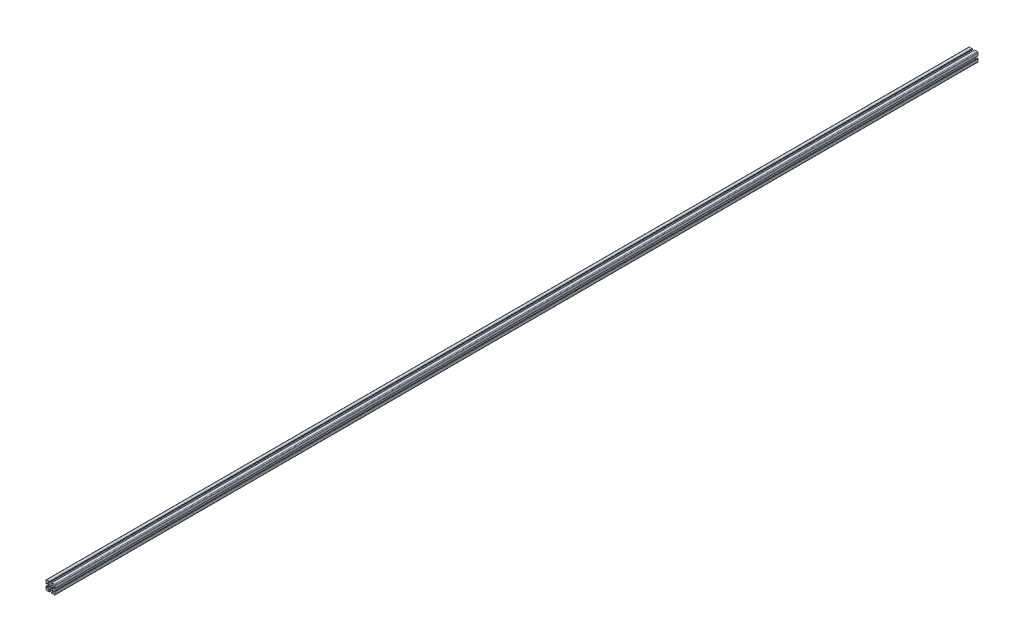
SolidWorks part; units mm, degrees
material "6061 Alloy"
ref_plane "Front Plane" through (0, 0, 0) normal (0, 0, 1) x (1, 0, 0)
ref_plane "Top Plane" through (0, 0, 0) normal (0, 1, 0) x (1, 0, 0)
ref_plane "Right Plane" through (0, 0, 0) normal (1, 0, 0) x (0, 0, -1)
sketch "Sketch1" plane through (0, 0, 0) normal (0, 0, 1) x (1, 0, 0)
  line L0 (0, 19.7407) -> (0, -19.7407) construction
  line L1 (19.0335, 0) -> (-20.7246, 0) construction
  line L2 (-8.715, -15.5246) -> (-5.63, -15.5246)
  line L3 (-10.285, -13.9546) -> (-10.285, -13.4925)
  line L4 (-6.2171, -9.1098) -> (-10.0624, -12.9551)
  line L5 (2.7773, -7.685) -> (-2.7773, -7.685)
  line L6 (10.0624, -12.9551) -> (6.2171, -9.1098)
  line L7 (10.285, -13.9546) -> (10.285, -13.4925)
  line L8 (5.63, -15.5246) -> (8.715, -15.5246)
  line L9 (4.06, -18.43) -> (4.06, -17.0946)
  line L10 (-4.06, -18.43) -> (-4.06, -17.0946)
  line L11 (15.68, -8.7154) -> (15.68, -5.63)
  line L12 (-14.11, -10.2854) -> (-13.8169, -10.2854)
  line L13 (20, -16.83) -> (20, -5.63)
  line L14 (20, 5.63) -> (20, 13.0011)
  line L15 (-16.83, 20) -> (-5.63, 20)
  line L16 (5.63, 20) -> (12.9796, 20)
  line L18 (-8.715, 15.5246) -> (-5.63, 15.5246)
  line L19 (-20, -17.0184) -> (-20, -5.7579)
  line L20 (-20, 5.573) -> (-20, 13.0045)
  line L21 (-15.68, -8.7154) -> (-15.68, -5.7579)
  line L23 (-16.6746, -20) -> (-5.63, -20)
  line L24 (5.63, -20) -> (13, -20)
  line L53 (14.11, -10.2854) -> (13.6201, -10.2854)
  line L54 (13.1637, -9.947) -> (9.0762, -5.8595)
  line L55 (7.685, -2.5008) -> (7.685, 2.5008)
  line L56 (9.0762, 5.8595) -> (13.2795, 10.0628)
  line L57 (13.8169, 10.2854) -> (14.11, 10.2854)
  line L58 (15.68, 8.7154) -> (15.68, 5.63)
  line L59 (17.25, 4.06) -> (18.43, 4.06)
  line L61 (20, 13.0011) -> (20, 16.83)
  line L62 (16.83, 20) -> (12.9796, 20)
  line L64 (4.06, 18.43) -> (4.06, 17.0946)
  line L65 (5.63, 15.5246) -> (8.715, 15.5246)
  line L66 (10.285, 13.9546) -> (10.285, 13.4925)
  line L67 (10.0624, 12.9551) -> (6.2171, 9.1098)
  line L68 (2.7773, 7.685) -> (-2.7773, 7.685)
  line L69 (-6.2171, 9.1098) -> (-10.0624, 12.9551)
  line L70 (-10.285, 13.4925) -> (-10.285, 13.9546)
  line L72 (-4.06, 17.0946) -> (-4.06, 18.43)
  line L75 (-20, 16.83) -> (-20, 13.0045)
  line L77 (-18.43, 4.003) -> (-17.25, 4.003)
  line L78 (-15.68, 5.573) -> (-15.68, 8.4757)
  line L79 (-14.0552, 10.0447) -> (-13.7199, 10.033)
  line L80 (-13.0405, 9.8238) -> (-9.0762, 5.8595)
  line L81 (-7.685, 2.5008) -> (-7.685, -2.5008)
  line L82 (-9.0762, -5.8595) -> (-13.2795, -10.0628)
  line L85 (-17.25, -4.1204) -> (-18.43, -4.1204)
  line L100 (13, -20) -> (16.83, -20)
  line L103 (18.43, -4.06) -> (17.25, -4.06)
  arc A0 (-5.63, -15.5246) -> (-4.06, -17.0946) centre (-5.63, -17.0946) cw
  arc A1 (-8.715, -15.5246) -> (-10.285, -13.9546) centre (-8.715, -13.9546) cw
  arc A2 (-10.285, -13.4925) -> (-10.0624, -12.9551) centre (-9.525, -13.4925) cw
  arc A3 (-6.2171, -9.1098) -> (-2.7773, -7.685) centre (-2.7773, -12.5496) cw
  arc A4 (2.7773, -7.685) -> (6.2171, -9.1098) centre (2.7773, -12.5496) cw
  arc A5 (10.0624, -12.9551) -> (10.285, -13.4925) centre (9.525, -13.4925) cw
  arc A6 (10.285, -13.9546) -> (8.715, -15.5246) centre (8.715, -13.9546) cw
  arc A7 (4.06, -17.0946) -> (5.63, -15.5246) centre (5.63, -17.0946) cw
  arc A8 (5.63, -20) -> (4.06, -18.43) centre (5.63, -18.43) cw
  arc A9 (-4.06, -18.43) -> (-5.63, -20) centre (-5.63, -18.43) cw
  circle A45 centre (0, 0) radius 3.4
  arc A46 (17.25, -4.06) -> (15.68, -5.63) centre (17.25, -5.63) ccw
  arc A47 (14.11, -10.2854) -> (15.68, -8.7154) centre (14.11, -8.7154) ccw
  arc A48 (13.1637, -9.947) -> (13.6201, -10.2854) centre (13.8117, -9.55) ccw
  arc A49 (7.685, -2.5008) -> (9.0762, -5.8595) centre (12.435, -2.5008) ccw
  arc A50 (9.0762, 5.8595) -> (7.685, 2.5008) centre (12.435, 2.5008) ccw
  arc A51 (13.8169, 10.2854) -> (13.2795, 10.0628) centre (13.8169, 9.5254) ccw
  arc A52 (15.68, 8.7154) -> (14.11, 10.2854) centre (14.11, 8.7154) ccw
  arc A53 (15.68, 5.63) -> (17.25, 4.06) centre (17.25, 5.63) ccw
  arc A54 (18.43, 4.06) -> (20, 5.63) centre (18.43, 5.63) ccw
  arc A55 (20, 16.83) -> (16.83, 20) centre (16.83, 16.83) ccw
  arc A56 (5.63, 20) -> (4.06, 18.43) centre (5.63, 18.43) ccw
  arc A57 (4.06, 17.0946) -> (5.63, 15.5246) centre (5.63, 17.0946) ccw
  arc A58 (10.285, 13.9546) -> (8.715, 15.5246) centre (8.715, 13.9546) ccw
  arc A59 (10.0624, 12.9551) -> (10.285, 13.4925) centre (9.525, 13.4925) ccw
  arc A60 (2.7773, 7.685) -> (6.2171, 9.1098) centre (2.7773, 12.5496) ccw
  arc A61 (-6.2171, 9.1098) -> (-2.7773, 7.685) centre (-2.7773, 12.5496) ccw
  arc A62 (-10.285, 13.4925) -> (-10.0624, 12.9551) centre (-9.525, 13.4925) ccw
  arc A63 (-8.715, 15.5246) -> (-10.285, 13.9546) centre (-8.715, 13.9546) ccw
  arc A64 (-5.63, 15.5246) -> (-4.06, 17.0946) centre (-5.63, 17.0946) ccw
  arc A65 (-4.06, 18.43) -> (-5.63, 20) centre (-5.63, 18.43) ccw
  arc A66 (-16.83, 20) -> (-20, 16.83) centre (-16.83, 16.83) ccw
  arc A67 (-20, 5.573) -> (-18.43, 4.003) centre (-18.43, 5.573) ccw
  arc A68 (-17.25, 4.003) -> (-15.68, 5.573) centre (-17.25, 5.573) ccw
  arc A69 (-14.0552, 10.0447) -> (-15.68, 8.4757) centre (-14.11, 8.4757) ccw
  arc A70 (-13.0405, 9.8238) -> (-13.7199, 10.033) centre (-13.5779, 9.2864) ccw
  arc A71 (-7.685, 2.5008) -> (-9.0762, 5.8595) centre (-12.435, 2.5008) ccw
  arc A72 (-9.0762, -5.8595) -> (-7.685, -2.5008) centre (-12.435, -2.5008) ccw
  arc A73 (-13.8169, -10.2854) -> (-13.2795, -10.0628) centre (-13.8169, -9.5254) ccw
  arc A74 (-15.68, -8.7154) -> (-14.11, -10.2854) centre (-14.11, -8.7154) ccw
  arc A75 (-15.68, -5.7579) -> (-17.25, -4.1204) centre (-17.2485, -5.6904) ccw
  arc A76 (-18.43, -4.1204) -> (-20, -5.7579) centre (-18.4315, -5.6904) ccw
  arc A77 (-20, -17.0184) -> (-16.6746, -20) centre (-16.8354, -16.8341) ccw
  arc A88 (16.83, -20) -> (20, -16.83) centre (16.83, -16.83) ccw
  arc A89 (20, -5.63) -> (18.43, -4.06) centre (18.43, -5.63) ccw
  dimension "D2" = 6.8
  dimension "D7" = 20.57
  dimension "D1" = 40
  dimension "D3" = 4.32
  dimension "D4" = 15.37
  dimension "D5" = 20
  dimension "D6" = 4.32
  dimension "D9" = 15.37
extrude "Extrude1" add sketch "Sketch1" against normal blind 4000
